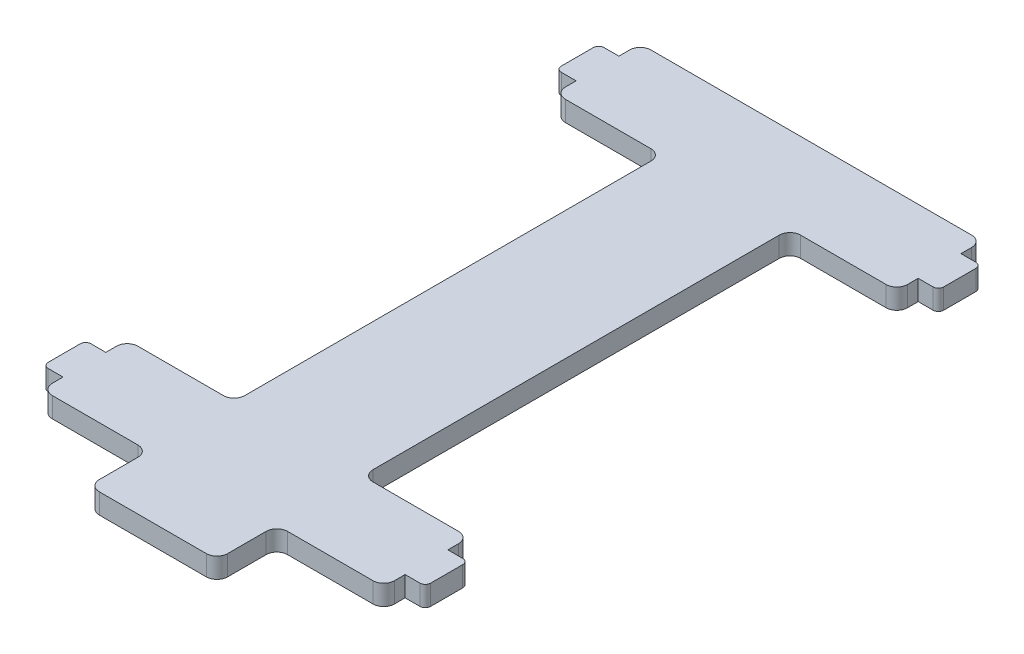
SolidWorks part; units mm, degrees
ref_plane "Front Plane" through (0, 0, 0) normal (0, 0, 1) x (1, 0, 0)
ref_plane "Top Plane" through (0, 0, 0) normal (0, 1, 0) x (1, 0, 0)
ref_plane "Right Plane" through (0, 0, 0) normal (1, 0, 0) x (0, 0, -1)
sketch "Sketch1" plane through (0, 0, 0) normal (0, 1, 0) x (1, 0, 0)
  line L0 (25.4, 31.75) -> (9.525, 31.75)
  line L1 (-25.4, -44.45) -> (-9.525, -44.45)
  line L2 (-25.4, -44.45) -> (-25.4, -31.75)
  line L4 (25.4, -44.45) -> (25.4, -31.75)
  line L5 (-25.4, -44.45) -> (25.4, 44.45) construction
  line L6 (-25.4, 44.45) -> (25.4, -44.45) construction
  line L7 (9.525, 31.75) -> (9.525, -31.75)
  line L8 (9.525, -31.75) -> (25.4, -31.75)
  line L9 (-25.4, -31.75) -> (-9.525, -31.75)
  line L10 (-9.525, -31.75) -> (-9.525, 31.75)
  line L11 (-9.525, 31.75) -> (-25.4, 31.75)
  line L12 (0, -44.45) -> (0, 44.45) construction
  line L13 (-25.4, -31.75) -> (-25.4, 31.75) construction
  line L14 (-25.4, 31.75) -> (-25.4, 44.45)
  line L15 (25.4, -31.75) -> (25.4, 31.75) construction
  line L16 (25.4, 31.75) -> (25.4, 44.45)
  line L20 (0, -44.45) -> (9.525, -44.45) construction
  line L21 (9.525, -44.45) -> (25.4, -44.45)
  line L22 (-9.525, -44.45) -> (0, -44.45) construction
  line L26 (-9.525, 44.45) -> (0, 44.45) construction
  line L27 (-25.4, 44.45) -> (25.4, 44.45)
  line L28 (0, 44.45) -> (-25.4, 44.45) construction
  line L29 (-9.525, -44.45) -> (-9.525, -53.34)
  line L30 (-9.525, -53.34) -> (9.525, -53.34)
  line L31 (9.525, -53.34) -> (9.525, -44.45)
  point P0 (0, 0)
  dimension "D1" = 50.8
  dimension "D2" = 88.9
  dimension "D3" = 12.7
  dimension "D4" = 12.7
  dimension "D5" = 19.05
  dimension "D6" = 8.89
  dimension "D7" = 19.05
extrude "Boss-Extrude1" add sketch "Sketch1" along normal mid plane 3
fillet "Fillet1" radius 1.5875 16 edges at (25.4, 0, -31.75) (9.525, 0, -31.75) (9.525, 0, 31.75) (25.4, 0, 31.75) (-25.4, 0, 31.75) (-9.525, 0, 31.75) (-9.525, 0, -31.75) (-25.4, 0, -31.75) (-25.4, 0, 44.45) (25.4, 0, 44.45) (25.4, 0, -44.45) (9.525, 0, 44.45) (9.525, 0, 53.34) (-9.525, 0, 44.45) (-25.4, 0, -44.45) (-9.525, 0, 53.34)
sketch "Sketch2" plane through (0, 1.5, 0) normal (0, 1, 0) x (1, 0, 0)
  line L5 (-25.4, 31.75) -> (-25.4, 44.45) construction
  line L6 (-26.9, 38.1) -> (-25.4, 38.1) construction
  line L12 (-25.4, -44.45) -> (-25.4, -31.75) construction
  line L13 (25.4, 31.75) -> (25.4, 44.45) construction
  line L14 (25.4, -44.45) -> (25.4, -31.75) construction
  line L15 (-26.9, -38.1) -> (-25.4, -38.1) construction
  line B0 (-28.4, 34.925) -> (-25.4, 34.925)
  line B1 (-28.4, 34.925) -> (-28.4, 41.275)
  line B2 (-28.4, 41.275) -> (-25.4, 41.275)
  line B3 (-25.4, 34.925) -> (-25.4, 41.275)
  line B4 (-28.4, 34.925) -> (-25.4, 41.275) construction
  line B5 (-28.4, 41.275) -> (-25.4, 34.925) construction
  line B6 (25.4, 34.925) -> (28.4, 34.925)
  line B7 (25.4, 34.925) -> (25.4, 41.275)
  line B8 (25.4, 41.275) -> (28.4, 41.275)
  line B9 (28.4, 34.925) -> (28.4, 41.275)
  line B10 (25.4, -41.275) -> (28.4, -41.275)
  line B11 (25.4, -41.275) -> (25.4, -34.925)
  line B12 (25.4, -34.925) -> (28.4, -34.925)
  line B13 (28.4, -41.275) -> (28.4, -34.925)
  line B14 (-28.4, -41.275) -> (-25.4, -41.275)
  line B15 (-28.4, -41.275) -> (-28.4, -34.925)
  line B16 (-28.4, -34.925) -> (-25.4, -34.925)
  line B17 (-25.4, -41.275) -> (-25.4, -34.925)
sketch_block_instance "Block1-1"
sketch_block "Block1" parameters "D1"=6.35, "D2"=3
sketch_block_instance "Block1-2"
sketch_block_instance "Block1-3"
sketch_block_instance "Block1-4"
extrude "Boss-Extrude2" add sketch "Sketch2" against normal up to surface (3 mm away) up to face at (0, -1.5, 12.2238)
fillet "Fillet2" radius 0.7937 8 edges at (-28.4, 0, 41.275) (-28.4, 0, 34.925) (28.4, 0, 34.925) (28.4, 0, 41.275) (28.4, 0, -41.275) (28.4, 0, -34.925) (-28.4, 0, -41.275) (-28.4, 0, -34.925)
